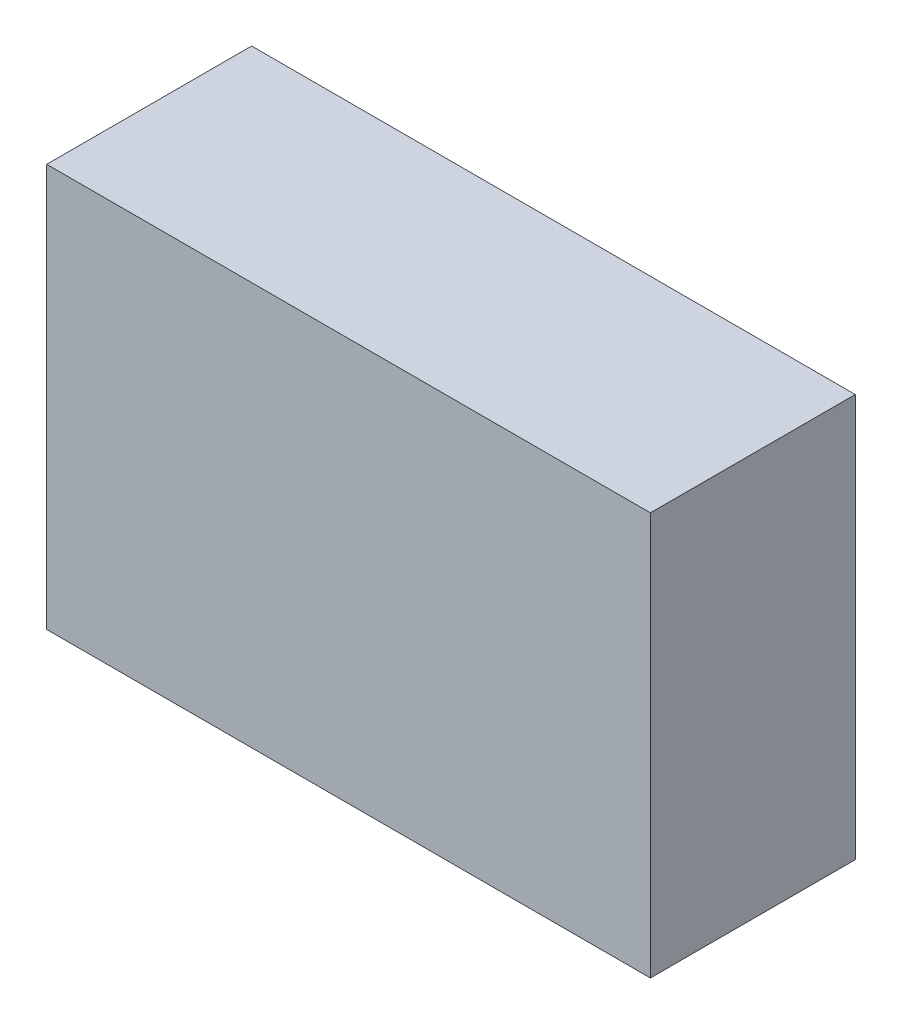
SolidWorks part; units mm, degrees
ref_plane "Front Plane" through (0, 0, 0) normal (0, 0, 1) x (1, 0, 0)
ref_plane "Top Plane" through (0, 0, 0) normal (0, 1, 0) x (1, 0, 0)
ref_plane "Right Plane" through (0, 0, 0) normal (1, 0, 0) x (0, 0, -1)
sketch "Sketch1" plane through (0, 0, 0) normal (0, 0, 1) x (1, 0, 0)
  line L0 (-1.473, 0.983) -> (1.473, 0.983)
  line L1 (1.473, 0.983) -> (1.473, -0.983)
  line L2 (1.473, -0.983) -> (-1.473, -0.983)
  line L3 (-1.473, -0.983) -> (-1.473, 0.983)
extrude "Component_Outline" add sketch "Sketch1" along normal blind 1 separate body
sketch3d "3DSketch1"
  line L0 (0, 0, 0) -> (1, 0, 0)
  line L1 (0, 0, 0) -> (0, 1, 0)
  line L2 (0, 0, 0) -> (0, 0, 1)
  point P0 (0, 0, 0)
